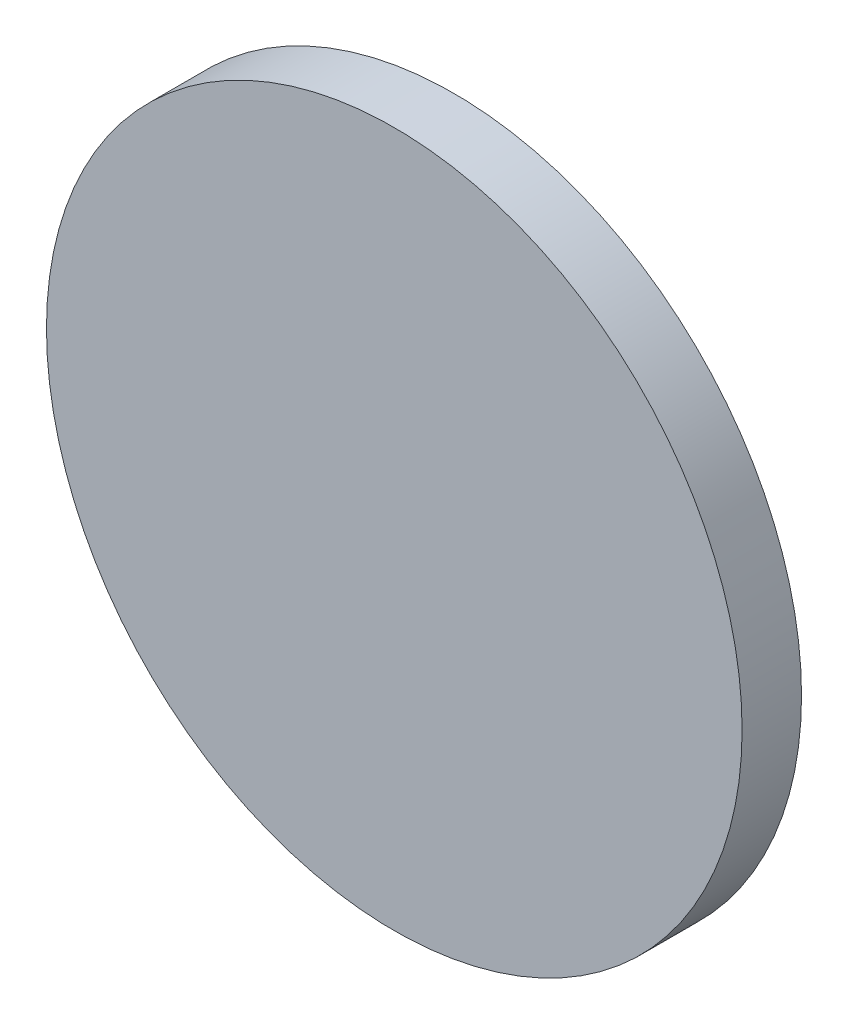
SolidWorks part; units mm, degrees
ref_plane "Plan de face" through (0, 0, 0) normal (0, 0, 1) x (1, 0, 0)
ref_plane "Plan de dessus" through (0, 0, 0) normal (0, 1, 0) x (1, 0, 0)
ref_plane "Plan de droite" through (0, 0, 0) normal (1, 0, 0) x (0, 0, -1)
sketch "Esquisse1" plane through (0, 0, 0) normal (0, 0, 1) x (1, 0, 0)
  circle A0 centre (0, 0) radius 12.875
  dimension "D1" = 25.75
extrude "Boss.-Extru.1" add sketch "Esquisse1" along normal blind 2.2
sketch "Esquisse2" plane through (0, 0, 0) normal (0, 0, -1) x (-1, 0, 0)
  line L0 (-12.7394, -1.8635) -> (12.7394, -1.8635) construction
  circle A0 centre (0, 0) radius 12.875 construction
  text T0 "<b>2</b>" font "Century Gothic" height 5
  point P5 (0, 0)
extrude "Enlèv. mat.-Extru.1" cut sketch "Esquisse2" against normal blind 0.15
